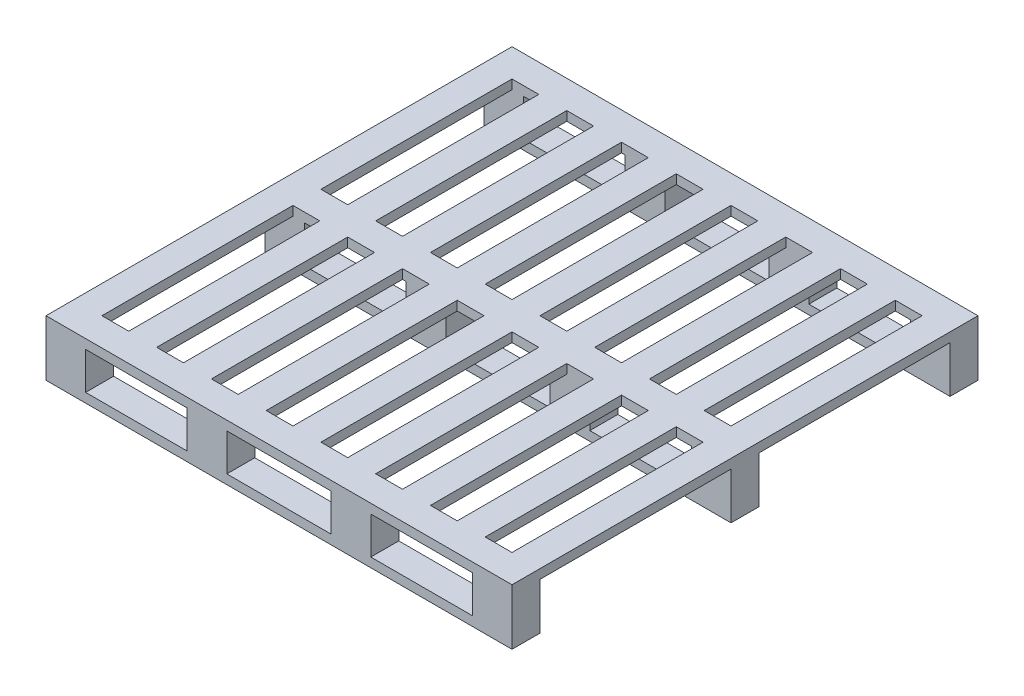
SolidWorks part; units mm, degrees
ref_plane "Front Plane" through (0, 0, 0) normal (0, 0, 1) x (1, 0, 0)
ref_plane "Top Plane" through (0, 0, 0) normal (0, 1, 0) x (1, 0, 0)
ref_plane "Right Plane" through (0, 0, 0) normal (1, 0, 0) x (0, 0, -1)
sketch "Sketch1" plane through (0, 0, 0) normal (0, 1, 0) x (1, 0, 0)
  line L1 (-500, 500) -> (500, 500) construction
  line L2 (-500, 500) -> (-500, -500) construction
  line L3 (-500, -500) -> (500, -500) construction
  line L4 (500, 500) -> (500, -500) construction
  line L5 (-500, 500) -> (500, -500) construction
  line L6 (-500, -500) -> (500, 500) construction
  line L7 (-500, 500) -> (-440, 500)
  line L8 (-500, 500) -> (-500, -500)
  line L9 (-500, -500) -> (-440, -500)
  line L10 (-440, 500) -> (-440, -500)
  line L11 (500, -500) -> (440, -500)
  line L12 (500, -500) -> (500, 500)
  line L13 (500, 500) -> (440, 500)
  line L14 (440, -500) -> (440, 500)
  line L15 (-186.67, 500) -> (-126.67, 500)
  line L16 (-186.67, 500) -> (-186.67, -500)
  line L17 (-186.67, -500) -> (-126.67, -500)
  line L18 (-126.67, 500) -> (-126.67, -500)
  line L19 (126.67, 500) -> (186.67, 500)
  line L20 (126.67, 500) -> (126.67, -500)
  line L21 (126.67, -500) -> (186.67, -500)
  line L22 (186.67, 500) -> (186.67, -500)
  point P0 (0, 0)
  dimension "D1" = 1000
  dimension "D2" = 1000
  dimension "D3" = 60
  dimension "D4" = 60
  dimension "D5" = 60
  dimension "D6" = 60
  dimension "D7" = 253.33
  dimension "D8" = 253.33
extrude "Boss-Extrude1" add sketch "Sketch1" along normal blind 20
sketch "Sketch2" plane through (0, 0, 0) normal (0, 1, 0) x (1, 0, 0)
  line L1 (-500, 500) -> (500, 500) construction
  line L2 (-500, 500) -> (-500, -500) construction
  line L3 (-500, -500) -> (500, -500) construction
  line L4 (500, 500) -> (500, -500) construction
  line L5 (-500, 500) -> (500, -500) construction
  line L6 (-500, -500) -> (500, 500) construction
  line L7 (-500, -500) -> (500, -500)
  line L8 (-500, -500) -> (-500, -440)
  line L9 (-500, -440) -> (500, -440)
  line L10 (500, -500) -> (500, -440)
  line L11 (-500, 500) -> (500, 500)
  line L12 (-500, 500) -> (-500, 440)
  line L13 (-500, 440) -> (500, 440)
  line L14 (500, 500) -> (500, 440)
  line L15 (-500, -30) -> (500, -30)
  line L16 (-500, -30) -> (-500, 30)
  line L17 (-500, 30) -> (500, 30)
  line L18 (500, -30) -> (500, 30)
  point P0 (0, 0)
  dimension "D1" = 60
  dimension "D2" = 60
  dimension "D3" = 60
  dimension "D4" = 470
extrude "Boss-Extrude2" add sketch "Sketch2" along normal blind 20
sketch "Sketch3" plane through (0, 20, 0) normal (0, 1, 0) x (1, 0, 0)
  line L0 (-500, 0) -> (500, 0) construction
  line L1 (-500, 500) -> (-500, -500) construction
  line L2 (500, -500) -> (500, 500) construction
  line L3 (440, -440) -> (186.67, -440) construction
  line L4 (500, -500) -> (415, -500)
  line L5 (500, -500) -> (500, -440)
  line L6 (500, -440) -> (415, -440)
  line L7 (415, -500) -> (415, -440)
  line L8 (186.67, 440) -> (440, 440) construction
  line L9 (500, 500) -> (415, 500)
  line L10 (500, 500) -> (500, 440)
  line L11 (500, 440) -> (415, 440)
  line L12 (415, 500) -> (415, 440)
  line L13 (440, 30) -> (186.67, 30) construction
  line L14 (500, -30) -> (415, -30)
  line L15 (500, -30) -> (500, 30)
  line L16 (500, 30) -> (415, 30)
  line L17 (415, -30) -> (415, 30)
  line L18 (500, -30) -> (415, 30) construction
  line L19 (500, 30) -> (415, -30) construction
  line L20 (-500, -500) -> (500, -500) construction
  line L21 (112, -500) -> (197, -500)
  line L22 (112, -500) -> (112, -440)
  line L23 (112, -440) -> (197, -440)
  line L24 (197, -500) -> (197, -440)
  line L25 (-126.67, -30) -> (126.67, -30) construction
  line L26 (112, -30) -> (197, -30)
  line L27 (112, -30) -> (112, 30)
  line L28 (112, 30) -> (197, 30)
  line L29 (197, -30) -> (197, 30)
  line L30 (-126.67, 440) -> (126.67, 440) construction
  line L31 (112, 440) -> (197, 440)
  line L32 (112, 440) -> (112, 500)
  line L33 (112, 500) -> (197, 500)
  line L34 (197, 440) -> (197, 500)
  line L35 (500, 500) -> (-500, 500) construction
  line L38 (0, -500) -> (0, 500) construction
  line L39 (-500, 30) -> (-415, -30) construction
  line L40 (-500, -30) -> (-415, 30) construction
  line L41 (-197, 440) -> (-197, 500)
  line L42 (-112, 500) -> (-197, 500)
  line L43 (-112, 440) -> (-112, 500)
  line L44 (-112, 440) -> (-197, 440)
  line L45 (-197, -30) -> (-197, 30)
  line L46 (-112, 30) -> (-197, 30)
  line L47 (-112, -30) -> (-112, 30)
  line L48 (-112, -30) -> (-197, -30)
  line L49 (-197, -500) -> (-197, -440)
  line L50 (-112, -440) -> (-197, -440)
  line L51 (-112, -500) -> (-112, -440)
  line L52 (-112, -500) -> (-197, -500)
  line L53 (-415, -30) -> (-415, 30)
  line L54 (-500, 30) -> (-415, 30)
  line L55 (-500, -30) -> (-500, 30)
  line L56 (-500, -30) -> (-415, -30)
  line L57 (-415, 500) -> (-415, 440)
  line L58 (-500, 440) -> (-415, 440)
  line L59 (-500, 500) -> (-500, 440)
  line L60 (-500, 500) -> (-415, 500)
  line L61 (-415, -500) -> (-415, -440)
  line L62 (-500, -440) -> (-415, -440)
  line L63 (-500, -500) -> (-500, -440)
  line L64 (-500, -500) -> (-415, -500)
  point P20 (457.5, 0)
  point P73 (-457.5, 0)
  dimension "D1" = 85
  dimension "D2" = 85
  dimension "D3" = 85
  dimension "D4" = 85
  dimension "D5" = 85
  dimension "D6" = 85
  dimension "D7" = 303
extrude "Boss-Extrude3" add sketch "Sketch3" along normal blind 80
sketch "Sketch4" plane through (0, 100, 0) normal (0, 1, 0) x (1, 0, 0)
  line L1 (-500, -500) -> (500, -500)
  line L2 (-500, -500) -> (-500, -440)
  line L3 (-500, -440) -> (500, -440)
  line L4 (500, -500) -> (500, -440)
  line L5 (-500, -30) -> (500, -30)
  line L6 (-500, -30) -> (-500, 30)
  line L7 (-500, 30) -> (500, 30)
  line L8 (500, -30) -> (500, 30)
  line L9 (-500, 440) -> (500, 440)
  line L10 (-500, 440) -> (-500, 500)
  line L11 (-500, 500) -> (500, 500)
  line L12 (500, 440) -> (500, 500)
extrude "Boss-Extrude4" add sketch "Sketch4" along normal blind 20
sketch "Sketch5" plane through (0, 120, 0) normal (0, 1, 0) x (1, 0, 0)
  line L0 (500, 500) -> (-500, 500) construction
  line L1 (-500, -500) -> (-440, -500)
  line L2 (-500, -500) -> (-500, 500)
  line L3 (-500, 500) -> (-440, 500)
  line L4 (-440, -500) -> (-440, 500)
  line L5 (-322.5, -500) -> (-322.5, 500)
  line L6 (-382.5, 500) -> (-322.5, 500)
  line L7 (-382.5, -500) -> (-382.5, 500)
  line L8 (-382.5, -500) -> (-322.5, -500)
  line L9 (-205, -500) -> (-205, 500)
  line L10 (-265, 500) -> (-205, 500)
  line L11 (-265, -500) -> (-265, 500)
  line L12 (-265, -500) -> (-205, -500)
  line L13 (-87.5, -500) -> (-87.5, 500)
  line L14 (-147.5, 500) -> (-87.5, 500)
  line L15 (-147.5, -500) -> (-147.5, 500)
  line L16 (-147.5, -500) -> (-87.5, -500)
  line L17 (30, -500) -> (30, 500)
  line L18 (-30, 500) -> (30, 500)
  line L19 (-30, -500) -> (-30, 500)
  line L20 (-30, -500) -> (30, -500)
  line L21 (147.5, -500) -> (147.5, 500)
  line L22 (87.5, 500) -> (147.5, 500)
  line L23 (87.5, -500) -> (87.5, 500)
  line L24 (87.5, -500) -> (147.5, -500)
  line L25 (265, -500) -> (265, 500)
  line L26 (205, 500) -> (265, 500)
  line L27 (205, -500) -> (205, 500)
  line L28 (205, -500) -> (265, -500)
  line L29 (382.5, -500) -> (382.5, 500)
  line L30 (322.5, 500) -> (382.5, 500)
  line L31 (322.5, -500) -> (322.5, 500)
  line L32 (322.5, -500) -> (382.5, -500)
  line L34 (500, -500) -> (440, -500)
  line L35 (500, -500) -> (500, 500)
  line L36 (500, 500) -> (440, 500)
  line L37 (440, -500) -> (440, 500)
  dimension "D1" = 60
  dimension "D3" = 60
  dimension "D2" = 8
extrude "Boss-Extrude5" add sketch "Sketch5" against normal blind 20
sketch "Sketch6" plane through (500, 0, 0) normal (1, 0, 0) x (0, 0, -1)
  line L5 (-440, 20) -> (-30, 20)
  line L6 (-440, 20) -> (-440, 0)
  line L7 (-440, 0) -> (-30, 0)
  line L8 (-30, 20) -> (-30, 0)
  line L9 (30, 20) -> (440, 20)
  line L10 (30, 20) -> (30, 0)
  line L11 (30, 0) -> (440, 0)
  line L12 (440, 20) -> (440, 0)
extrude "Cut-Extrude1" cut sketch "Sketch6" against normal up to surface (1000 mm away) up to face at (-500, 60, 235)
